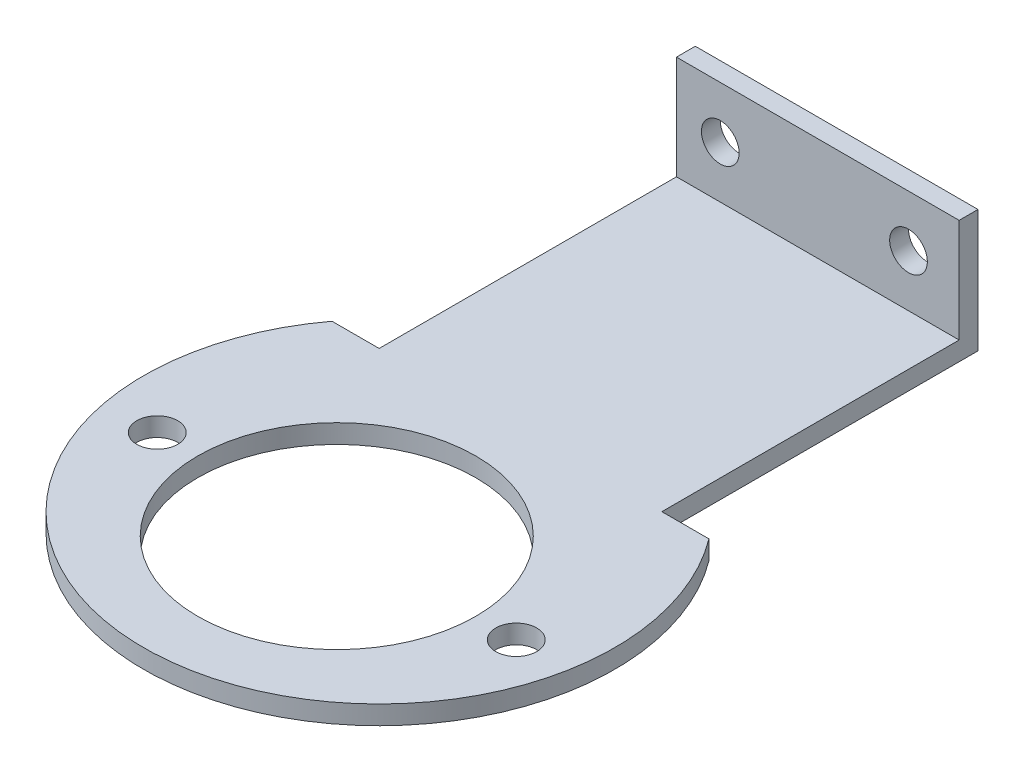
SolidWorks part; units mm, degrees
ref_plane "Front" through (0, 0, 0) normal (0, 0, 1) x (1, 0, 0)
ref_plane "Top" through (0, 0, 0) normal (0, 1, 0) x (1, 0, 0)
ref_plane "Right" through (0, 0, 0) normal (1, 0, 0) x (0, 0, -1)
sketch "Sketch1" plane through (0, 0, 0) normal (0, 1, 0) x (1, 0, 0)
  line L4 (-40, 30) -> (40, 30)
  circle A0 centre (0, 0) radius 50 construction
  arc A1 (-50, 0) -> (50, 0) centre (0, 0) ccw
  arc A3 (-40, 30) -> (-50, 0) centre (0, 0) ccw
  arc A4 (40, 30) -> (50, 0) centre (0, 0) cw
  point P12 (-50, 30)
  dimension "D1" = 100
  dimension "D2" = 30
extrude "Boss-Extrude1" add sketch "Sketch1" along normal blind 4
sketch "Sketch2" plane through (0, 4, 0) normal (0, 1, 0) x (1, 0, 0)
  line L0 (-38.1, 0) -> (-38.1, -9) construction
  line L1 (38.1, 0) -> (-38.1, 0) construction
  line L3 (38.1, 0) -> (38.1, -9) construction
  circle A4 centre (-38.1, -9) radius 4.35
  circle A5 centre (38.1, -9) radius 4.35
  point P11 (0, 0)
  dimension "D2" = 8.7
  dimension "D3" = 8.7
  dimension "D4" = 9
  dimension "D1" = 76.2
  dimension "D5" = 9
extrude "Cut-Extrude1" cut sketch "Sketch2" against normal blind 4
sketch "Sketch8" plane through (0, 0, -30) normal (0, 0, -1) x (-1, 0, 0)
  line L0 (0, 4) -> (0, 0) construction
  line L1 (-40, 4) -> (40, 4) construction
  line L2 (-40, 0) -> (40, 0) construction
  line L3 (-30, 4) -> (30, 4)
  line L4 (-30, 4) -> (-30, 0)
  line L5 (-30, 0) -> (30, 0)
  line L6 (30, 4) -> (30, 0)
  line L7 (-30, 4) -> (30, 0) construction
  line L8 (-30, 0) -> (30, 4) construction
  point P5 (0, 2)
  dimension "D1" = 60
extrude "Boss-Extrude4" add sketch "Sketch8" along normal blind 67.1
sketch "Sketch10" plane through (0, 4, 0) normal (0, 1, 0) x (1, 0, 0)
  line L0 (30, 97.1) -> (30, 30) construction
  line L1 (-30, 97.1) -> (30, 97.1)
  line L2 (-30, 97.1) -> (-30, 93.1)
  line L3 (-30, 93.1) -> (30, 93.1)
  line L4 (30, 97.1) -> (30, 93.1)
  line L5 (-30, 97.1) -> (30, 93.1) construction
  line L6 (-30, 93.1) -> (30, 97.1) construction
  point P4 (0, 95.1)
  dimension "D1" = 4
extrude "Boss-Extrude6" add sketch "Sketch10" along normal blind 22
sketch "Sketch11" plane through (0, 0, -97.1) normal (0, 0, -1) x (-1, 0, 0)
  line L2 (0, 15) -> (-19.25, 15) construction
  line L3 (0, 15) -> (20.7, 15) construction
  line L4 (-19.25, 15) -> (-19.25, 0) construction
  line L5 (-30, 0) -> (30, 0) construction
  circle A0 centre (-19.25, 15) radius 4
  circle A2 centre (20.7, 15) radius 4
  dimension "D1" = 8
  dimension "D3" = 20.7
  dimension "D4" = 8
  dimension "D2" = 19.25
  dimension "D5" = 15
extrude "Cut-Extrude2" cut sketch "Sketch11" against normal blind 20
sketch "Sketch12" plane through (0, 4, 0) normal (0, 1, 0) x (1, 0, 0)
  line L0 (-30, 30) -> (30, 30) construction
  line L1 (0, 30) -> (0, -9) construction
  circle A1 centre (0, -9) radius 29.5
  dimension "D1" = 39
  dimension "D2" = 59
extrude "Cut-Extrude3" cut sketch "Sketch12" against normal blind 10
